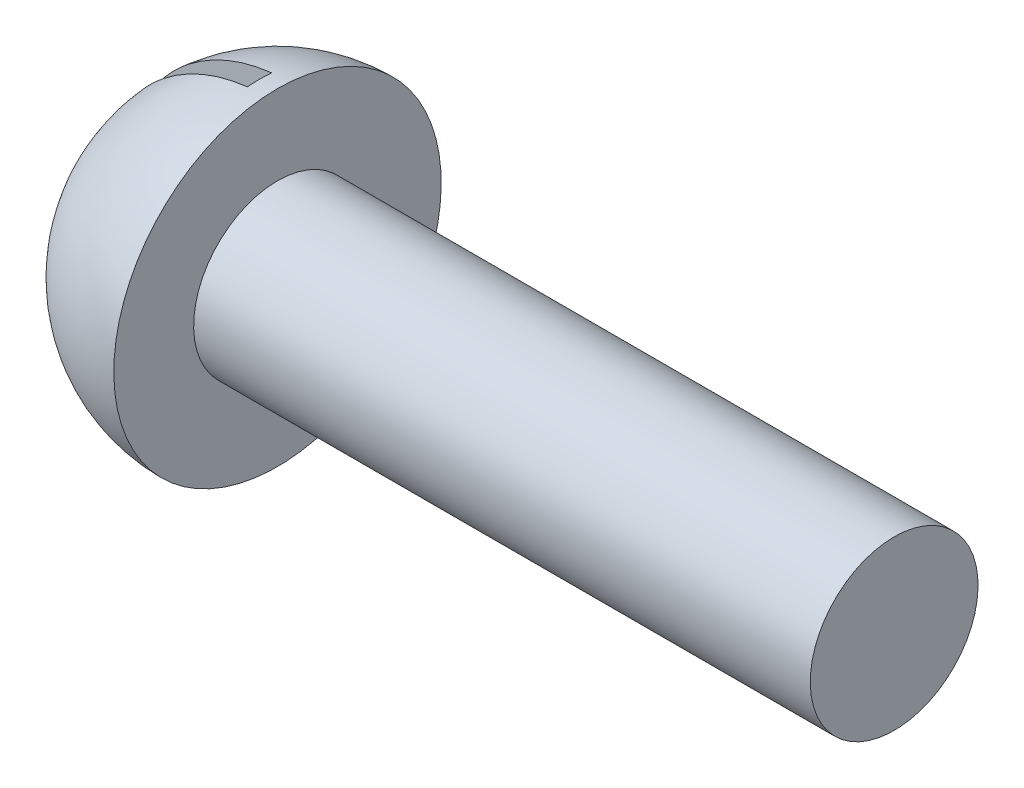
SolidWorks part; units mm, degrees
material "Plain Carbon Steel"
ref_plane "Front Plane" through (0, 0, 0) normal (0, 0, 1) x (1, 0, 0)
ref_plane "Top Plane" through (0, 0, 0) normal (0, 1, 0) x (1, 0, 0)
ref_plane "Right Plane" through (0, 0, 0) normal (1, 0, 0) x (0, 0, -1)
sketch "Sketch1" plane through (0, 0, 0) normal (0, 0, 1) x (1, 0, 0)
  line L1 (12.7, 0) -> (12.7, 1.7272)
  line L2 (12.7, 1.7272) -> (0, 1.7272)
  line L3 (0, 3.3715) -> (0, 1.7272)
  line L4 (-3.3715, 0) -> (12.7, 0)
  arc A0 (0, 3.3715) -> (-3.3715, 0) centre (0, 0) ccw
  dimension "D1" = 12.7
  dimension "D2" = 1.7272
ref_axis "Axis2" through (58.2164, 0, 0) along (-1, 0, 0)
revolve "Revolve3" add sketch "Sketch1" angle 360 about axis through (58.2164, 0, 0) along (-1, 0, 0)
ref_plane "Plane1" through (-3.3715, 0, 0) normal (-1, 0, 0) x (0, 0, 1)
sketch "Sketch2" plane through (-3.3715, 0, 0) normal (-1, 0, 0) x (0, 0, 1)
  line L1 (-0.25, 4.3418) -> (0.25, 4.3418)
  line L2 (-0.25, 4.3418) -> (-0.25, -4.4077)
  line L3 (-0.25, -4.4077) -> (0.25, -4.4077)
  line L4 (0.25, 4.3418) -> (0.25, -4.4077)
  point P4 (0, 4.3418)
  dimension "D1" = 0.5
extrude "Cut-Extrude1" cut sketch "Sketch2" against normal blind 3
